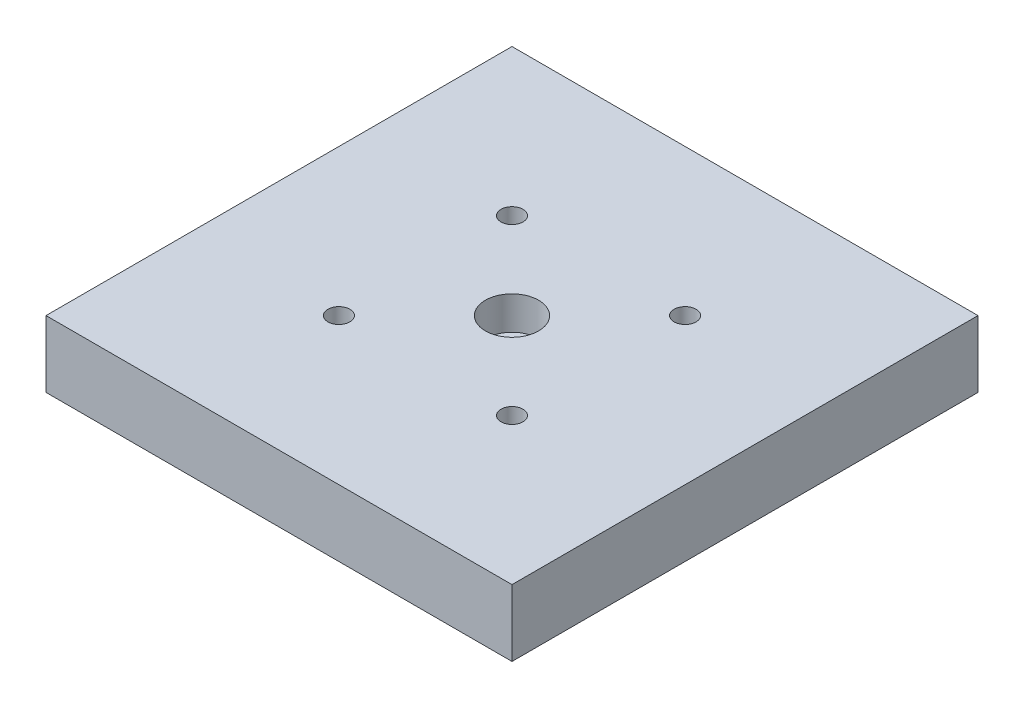
SolidWorks part; units mm, degrees
ref_plane "Front Plane" through (0, 0, 0) normal (0, 0, 1) x (1, 0, 0)
ref_plane "Top Plane" through (0, 0, 0) normal (0, 1, 0) x (1, 0, 0)
ref_plane "Right Plane" through (0, 0, 0) normal (1, 0, 0) x (0, 0, -1)
sketch "Sketch1" plane through (0, 0, 0) normal (0, 1, 0) x (1, 0, 0)
  line L1 (-35, -35) -> (35, -35)
  line L2 (-35, -35) -> (-35, 35)
  line L3 (-35, 35) -> (35, 35)
  line L4 (35, -35) -> (35, 35)
  line L5 (-35, -35) -> (35, 35) construction
  line L6 (-35, 35) -> (35, -35) construction
  point P0 (0, 0)
  dimension "D1" = 70
  dimension "D2" = 70
extrude "Boss-Extrude1" add sketch "Sketch1" along normal blind 10
sketch "Sketch2" plane through (0, 10, 0) normal (0, 1, 0) x (1, 0, 0)
  line L0 (-35, 35) -> (-35, -35) construction
  line L1 (35, 35) -> (-35, 35) construction
  circle A0 centre (-13, 13) radius 1.65
  circle A4 centre (13, 13) radius 1.65
  circle A5 centre (13, -13) radius 1.65
  circle A6 centre (-13, -13) radius 1.65
  dimension "D1" = 3.3
  dimension "D6" = 22
  dimension "D7" = 22
extrude "Cut-Extrude1" cut sketch "Sketch2" against normal blind 10
sketch "Sketch3" plane through (0, 10, 0) normal (0, 1, 0) x (1, 0, 0)
  circle A0 centre (0, 0) radius 4
  dimension "D1" = 8
extrude "Cut-Extrude2" cut sketch "Sketch3" against normal blind 5
